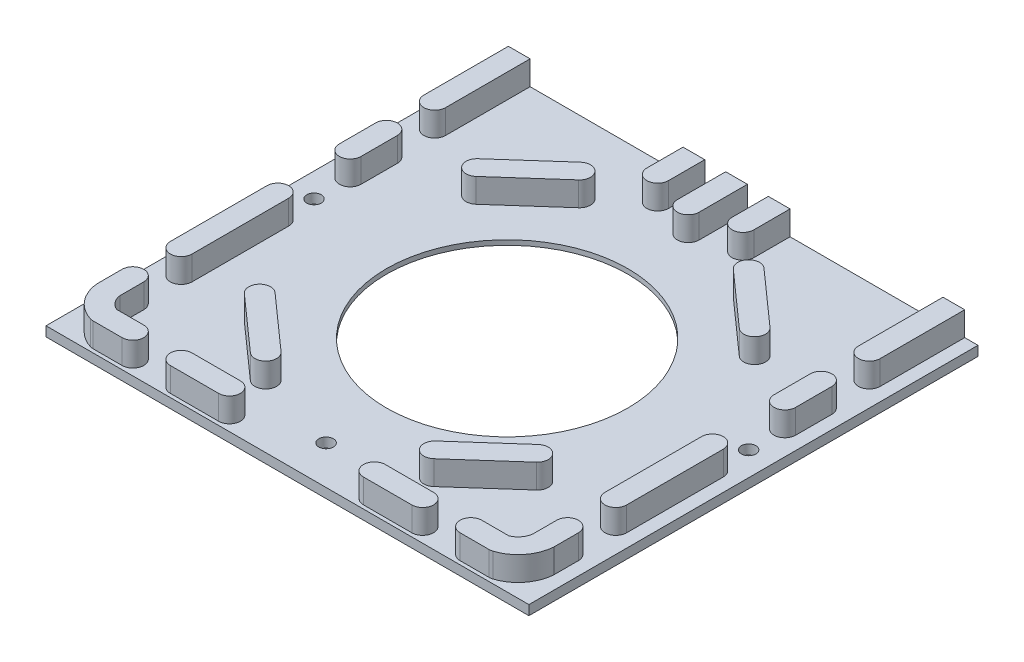
SolidWorks part; units mm, degrees
ref_plane "Front Plane" through (0, 0, 0) normal (0, 0, 1) x (1, 0, 0)
ref_plane "Top Plane" through (0, 0, 0) normal (0, 1, 0) x (1, 0, 0)
ref_plane "Right Plane" through (0, 0, 0) normal (1, 0, 0) x (0, 0, -1)
sketch "Sketch1" plane through (0, 0, 0) normal (0, 1, 0) x (1, 0, 0)
  line L1 (0, 0) -> (200, 0)
  line L2 (0, 0) -> (0, 190)
  line L3 (0, 190) -> (200, 190)
  line L4 (200, 0) -> (200, 190)
  dimension "D1" = 190
  dimension "D2" = 200
extrude "Boss-Extrude1" add sketch "Sketch1" along normal blind 4
sketch "Sketch3" plane through (0, 4, 0) normal (0, 1, 0) x (1, 0, 0)
  line L0 (0, 0) -> (18, 0)
  line L1 (0, 0) -> (200, 0) construction
  line L2 (18, 0) -> (18, 10)
  line L3 (0, 0) -> (0, 20)
  line L4 (0, 190) -> (0, 0) construction
  line L5 (0, 20) -> (10, 20)
  line L6 (10, 20) -> (10, 30) construction
  line L7 (5.5, 20) -> (5.5, 30)
  line L8 (14.5, 20) -> (14.5, 30)
  line L9 (18, 10) -> (30, 10) construction
  line L10 (18, 14.5) -> (30, 14.5)
  line L11 (18, 5.5) -> (30, 5.5)
  line L12 (0, 95) -> (200, 95) construction
  line L13 (200, 0) -> (200, 190) construction
  line L14 (100, 0) -> (100, 190) construction
  line L15 (200, 190) -> (0, 190) construction
  line L16 (10, 50) -> (10, 90) construction
  line L17 (5.5, 50) -> (5.5, 90)
  line L18 (14.5, 50) -> (14.5, 90)
  line L19 (50, 10) -> (70, 10) construction
  line L20 (50, 14.5) -> (70, 14.5)
  line L21 (50, 5.5) -> (70, 5.5)
  line L22 (190, 50) -> (190, 90) construction
  line L23 (194.5, 50) -> (194.5, 90)
  line L24 (185.5, 50) -> (185.5, 90)
  line L25 (190, 20) -> (190, 30) construction
  line L26 (194.5, 20) -> (194.5, 30)
  line L27 (185.5, 20) -> (185.5, 30)
  line L28 (182, 10) -> (170, 10) construction
  line L29 (182, 14.5) -> (170, 14.5)
  line L30 (182, 5.5) -> (170, 5.5)
  line L31 (150, 10) -> (130, 10) construction
  line L32 (150, 14.5) -> (130, 14.5)
  line L33 (150, 5.5) -> (130, 5.5)
  line L34 (10, 120) -> (10, 135) construction
  line L37 (157.5, 50) -> (135, 30) construction
  line L40 (154.5104, 53.3633) -> (132.0104, 33.3633)
  line L43 (160.4896, 46.6367) -> (137.9896, 26.6367)
  line L46 (157.5, 140) -> (135, 160) construction
  line L49 (154.5104, 136.6367) -> (132.0104, 156.6367)
  line L52 (160.4896, 143.3633) -> (137.9896, 163.3633)
  line L55 (5.5, 120) -> (5.5, 135)
  line L58 (200, 95) -> (200, 50) construction
  line L59 (200, 50) -> (0, 50) construction
  line L60 (200, 95) -> (200, 140) construction
  line L61 (200, 140) -> (0, 140) construction
  line L62 (42.5, 140) -> (65, 160) construction
  line L65 (45.4896, 136.6367) -> (67.9896, 156.6367)
  line L68 (39.5104, 143.3633) -> (62.0104, 163.3633)
  line L73 (42.5, 50) -> (65, 30) construction
  line L74 (45.4896, 53.3633) -> (67.9896, 33.3633)
  line L75 (39.5104, 46.6367) -> (62.0104, 26.6367)
  line L76 (100, 170) -> (100, 190) construction
  line L77 (95.5, 170) -> (95.5, 190)
  line L78 (104.5, 170) -> (104.5, 190)
  line L79 (82.3355, 175) -> (82.3355, 190) construction
  line L82 (77.8355, 175) -> (77.8355, 190)
  line L85 (10, 155) -> (10, 207.2046) construction
  line L86 (5.5, 155) -> (5.5, 207.2046)
  line L87 (14.5, 155) -> (14.5, 207.2046)
  line L88 (190, 155) -> (190, 207.2046) construction
  line L89 (194.5, 155) -> (194.5, 207.2046)
  line L90 (185.5, 155) -> (185.5, 207.2046)
  line L91 (86.8355, 175) -> (86.8355, 190)
  line L92 (117.6645, 175) -> (117.6645, 190) construction
  line L93 (122.1645, 175) -> (122.1645, 190)
  line L94 (113.1645, 175) -> (113.1645, 190)
  line L95 (14.5, 120) -> (14.5, 135)
  line L96 (190, 120) -> (190, 135) construction
  line L97 (194.5, 120) -> (194.5, 135)
  line L98 (185.5, 120) -> (185.5, 135)
  arc A1 (18, 10) -> (9.998, 20) centre (21.5097, 21.0101) cw construction
  arc A2 (5.5152, 19.6067) -> (16.6333, 5.7126) centre (21.5097, 21.0101) ccw
  arc A3 (14.4807, 20.3933) -> (19.3667, 14.2874) centre (21.5097, 21.0101) ccw
  arc A4 (14.4807, 20.3933) -> (5.5152, 19.6067) centre (9.998, 20) ccw
  arc A5 (16.6333, 5.7126) -> (19.3667, 14.2874) centre (18, 10) ccw
  arc A6 (5.5, 20) -> (14.5, 20) centre (10, 20) ccw
  arc A7 (14.5, 30) -> (5.5, 30) centre (10, 30) ccw
  arc A8 (18, 14.5) -> (18, 5.5) centre (18, 10) ccw
  arc A9 (30, 5.5) -> (30, 14.5) centre (30, 10) ccw
  arc A10 (5.5, 50) -> (14.5, 50) centre (10, 50) ccw
  arc A11 (14.5, 90) -> (5.5, 90) centre (10, 90) ccw
  arc A12 (50, 14.5) -> (50, 5.5) centre (50, 10) ccw
  arc A13 (70, 5.5) -> (70, 14.5) centre (70, 10) ccw
  arc A14 (194.5, 50) -> (185.5, 50) centre (190, 50) cw
  arc A15 (185.5, 90) -> (194.5, 90) centre (190, 90) cw
  arc A16 (194.5, 20) -> (185.5, 20) centre (190, 20) cw
  arc A17 (185.5, 30) -> (194.5, 30) centre (190, 30) cw
  arc A18 (182, 10) -> (190.002, 20) centre (178.4903, 21.0101) ccw construction
  arc A19 (194.4848, 19.6067) -> (183.3667, 5.7126) centre (178.4903, 21.0101) cw
  arc A20 (185.5193, 20.3933) -> (180.6333, 14.2874) centre (178.4903, 21.0101) cw
  arc A21 (185.5193, 20.3933) -> (194.4848, 19.6067) centre (190.002, 20) cw
  arc A22 (183.3667, 5.7126) -> (180.6333, 14.2874) centre (182, 10) cw
  arc A23 (182, 14.5) -> (182, 5.5) centre (182, 10) cw
  arc A24 (170, 5.5) -> (170, 14.5) centre (170, 10) cw
  arc A25 (150, 14.5) -> (150, 5.5) centre (150, 10) cw
  arc A26 (130, 5.5) -> (130, 14.5) centre (130, 10) cw
  circle A31 centre (100, 95) radius 50
  arc A44 (154.5104, 53.3633) -> (160.4896, 46.6367) centre (157.5, 50) cw
  arc A63 (45.4896, 53.3633) -> (39.5104, 46.6367) centre (42.5, 50) ccw
  arc A64 (62.0104, 26.6367) -> (67.9896, 33.3633) centre (65, 30) ccw
  arc A65 (137.9896, 26.6367) -> (132.0104, 33.3633) centre (135, 30) cw
  arc A66 (154.5104, 136.6367) -> (160.4896, 143.3633) centre (157.5, 140) ccw
  arc A67 (137.9896, 163.3633) -> (132.0104, 156.6367) centre (135, 160) ccw
  arc A68 (45.4896, 136.6367) -> (39.5104, 143.3633) centre (42.5, 140) cw
  arc A69 (62.0104, 163.3633) -> (67.9896, 156.6367) centre (65, 160) cw
  arc A70 (95.5, 170) -> (104.5, 170) centre (100, 170) ccw
  arc A71 (104.5, 190) -> (95.5, 190) centre (100, 190) ccw
  arc A76 (5.5, 155) -> (14.5, 155) centre (10, 155) ccw
  arc A77 (14.5, 207.2046) -> (5.5, 207.2046) centre (10, 207.2046) ccw
  arc A78 (194.5, 155) -> (185.5, 155) centre (190, 155) cw
  arc A79 (185.5, 207.2046) -> (194.5, 207.2046) centre (190, 207.2046) cw
  arc A80 (77.8355, 175) -> (86.8355, 175) centre (82.3355, 175) ccw
  arc A81 (86.8355, 190) -> (77.8355, 190) centre (82.3355, 190) ccw
  arc A82 (122.1645, 175) -> (113.1645, 175) centre (117.6645, 175) cw
  arc A83 (113.1645, 190) -> (122.1645, 190) centre (117.6645, 190) cw
  arc A84 (5.5, 120) -> (14.5, 120) centre (10, 120) ccw
  arc A85 (14.5, 135) -> (5.5, 135) centre (10, 135) ccw
  arc A86 (194.5, 120) -> (185.5, 120) centre (190, 120) cw
  arc A87 (185.5, 135) -> (194.5, 135) centre (190, 135) cw
  point P12 (12.4869, 13.79)
  point P17 (10, 25)
  point P25 (24, 10)
  point P40 (10, 70)
  point P47 (60, 10)
  point P54 (190, 70)
  point P61 (190, 25)
  point P69 (187.5131, 13.79)
  point P76 (176, 10)
  point P83 (140, 10)
  point P90 (10, 127.5)
  point P99 (146.25, 40)
  point P106 (146.25, 150)
  point P113 (53.75, 150)
  point P119 (100, 180)
  point P126 (82.3355, 182.5)
  point P133 (117.6645, 182.5)
  point P140 (10, 181.1023)
  point P147 (190, 181.1023)
  point P154 (190, 127.5)
  point P191 (53.75, 40)
  dimension "D4" = 4.5
  dimension "D8" = 4.5
  dimension "D11" = 4.5
  dimension "D16" = 100
  dimension "D19" = 4.5
  dimension "D22" = 4.5
  dimension "D24" = 16.0559
  dimension "D29" = 30
  dimension "D30" = 20
  dimension "D31" = 4.5
  dimension "D26" = 4.5
  dimension "D27" = 4.5
  dimension "D34" = 4.5
  dimension "D32" = 4.5
  dimension "D1" = 18
  dimension "D2" = 20
  dimension "D3" = 10
  dimension "D5" = 4.5
  dimension "D6" = 10
  dimension "D7" = 12
  dimension "D9" = 40
  dimension "D10" = 20
  dimension "D12" = 20
  dimension "D13" = 20
  dimension "D14" = 5
  dimension "D15" = 30
  dimension "D17" = 35
  dimension "D18" = 0
  dimension "D20" = 42.5
  dimension "D21" = 30
  dimension "D23" = 10
  dimension "D25" = 21.0101
  dimension "D28" = 15
  dimension "D33" = 15
  dimension "D35" = 35
extrude "Boss-Extrude2" add sketch "Sketch3" along normal blind 10
sketch "Sketch4" plane through (0, 0, 0) normal (0, 1, 0) x (1, 0, 0)
  line L0 (0, 0) -> (20, 0)
  line L1 (0, 0) -> (200, 0) construction
  line L2 (20, 0) -> (20, 10)
  line L3 (0, 0) -> (0, 20)
  line L5 (0, 20) -> (10, 20)
  line L6 (10, 20) -> (10, 30) construction
  line L7 (5, 20) -> (5, 30)
  line L8 (15, 20) -> (15, 30)
  line L9 (20, 10) -> (30, 10) construction
  line L10 (20, 15) -> (30, 15)
  line L11 (20, 5) -> (30, 5)
  line L12 (0, 95) -> (200, 95) construction
  line L14 (100, 0) -> (100, 170) construction
  line L16 (10, 50) -> (10, 72.5) construction
  line L17 (5, 50) -> (5, 72.5)
  line L18 (15, 50) -> (15, 72.5)
  line L19 (50, 10) -> (70, 10) construction
  line L20 (50, 15) -> (70, 15)
  line L21 (50, 5) -> (70, 5)
  line L22 (190, 50) -> (190, 72.5) construction
  line L23 (195, 50) -> (195, 72.5)
  line L24 (185, 50) -> (185, 72.5)
  line L25 (190, 20) -> (190, 30) construction
  line L26 (195, 20) -> (195, 30)
  line L27 (185, 20) -> (185, 30)
  line L28 (180, 10) -> (170, 10) construction
  line L29 (180, 15) -> (170, 15)
  line L30 (180, 5) -> (170, 5)
  line L31 (150, 10) -> (130, 10) construction
  line L32 (150, 15) -> (130, 15)
  line L33 (150, 5) -> (130, 5)
  line L34 (190, 140) -> (190, 117.5) construction
  line L35 (195, 140) -> (195, 117.5)
  line L36 (185, 140) -> (185, 117.5)
  line L37 (157.5, 50) -> (135, 30) construction
  line L40 (154.1782, 53.737) -> (131.6782, 33.737)
  line L43 (160.8218, 46.263) -> (138.3218, 26.263)
  line L46 (157.5, 140) -> (135, 160) construction
  line L49 (154.1782, 136.263) -> (131.6782, 156.263)
  line L52 (160.8218, 143.737) -> (138.3218, 163.737)
  line L55 (10, 140) -> (10, 117.5) construction
  line L56 (5, 140) -> (5, 117.5)
  line L57 (15, 140) -> (15, 117.5)
  line L58 (200, 95) -> (200, 50) construction
  line L59 (200, 50) -> (0, 50) construction
  line L60 (200, 95) -> (200, 140) construction
  line L61 (200, 140) -> (0, 140) construction
  line L62 (42.5, 140) -> (65, 160) construction
  line L65 (45.8218, 136.263) -> (68.3218, 156.263)
  line L68 (39.1782, 143.737) -> (61.6782, 163.737)
  line L73 (42.5, 50) -> (65, 30) construction
  line L74 (45.8218, 53.737) -> (68.3218, 33.737)
  line L75 (39.1782, 46.263) -> (61.6782, 26.263)
  line L76 (100, 150) -> (100, 170) construction
  line L77 (95, 150) -> (95, 170)
  line L78 (105, 150) -> (105, 170)
  line L79 (82.3355, 155) -> (82.3355, 170) construction
  line L82 (77.3355, 155) -> (77.3355, 170)
  line L85 (10, 165) -> (10, 207.2046) construction
  line L86 (5, 165) -> (5, 207.2046)
  line L87 (15, 165) -> (15, 207.2046)
  line L88 (190, 165) -> (190, 207.2046) construction
  line L89 (195, 165) -> (195, 207.2046)
  line L90 (185, 165) -> (185, 207.2046)
  line L91 (87.3355, 155) -> (87.3355, 170)
  line L92 (117.6645, 155) -> (117.6645, 170) construction
  line L93 (122.6645, 155) -> (122.6645, 170)
  line L94 (112.6645, 155) -> (112.6645, 170)
  arc A1 (20, 10) -> (9.9962, 20) centre (21.0059, 21.0101) cw construction
  arc A2 (5.0171, 19.5432) -> (19.5451, 5.0207) centre (21.0059, 21.0101) ccw
  arc A3 (14.9753, 20.4568) -> (20.4549, 14.9793) centre (21.0059, 21.0101) ccw
  arc A4 (14.9753, 20.4568) -> (5.0171, 19.5432) centre (9.9962, 20) ccw
  arc A5 (19.5451, 5.0207) -> (20.4549, 14.9793) centre (20, 10) ccw
  arc A6 (5, 20) -> (15, 20) centre (10, 20) ccw
  arc A7 (15, 30) -> (5, 30) centre (10, 30) ccw
  arc A8 (20, 15) -> (20, 5) centre (20, 10) ccw
  arc A9 (30, 5) -> (30, 15) centre (30, 10) ccw
  arc A10 (5, 50) -> (15, 50) centre (10, 50) ccw
  arc A11 (15, 72.5) -> (5, 72.5) centre (10, 72.5) ccw
  arc A12 (50, 15) -> (50, 5) centre (50, 10) ccw
  arc A13 (70, 5) -> (70, 15) centre (70, 10) ccw
  arc A14 (195, 50) -> (185, 50) centre (190, 50) cw
  arc A15 (185, 72.5) -> (195, 72.5) centre (190, 72.5) cw
  arc A16 (195, 20) -> (185, 20) centre (190, 20) cw
  arc A17 (185, 30) -> (195, 30) centre (190, 30) cw
  arc A18 (180, 10) -> (190.0038, 20) centre (178.9941, 21.0101) ccw construction
  arc A19 (194.9829, 19.5432) -> (180.4549, 5.0207) centre (178.9941, 21.0101) cw
  arc A20 (185.0247, 20.4568) -> (179.5451, 14.9793) centre (178.9941, 21.0101) cw
  arc A21 (185.0247, 20.4568) -> (194.9829, 19.5432) centre (190.0038, 20) cw
  arc A22 (180.4549, 5.0207) -> (179.5451, 14.9793) centre (180, 10) cw
  arc A23 (180, 15) -> (180, 5) centre (180, 10) cw
  arc A24 (170, 5) -> (170, 15) centre (170, 10) cw
  arc A25 (150, 15) -> (150, 5) centre (150, 10) cw
  arc A26 (130, 5) -> (130, 15) centre (130, 10) cw
  arc A27 (195, 140) -> (185, 140) centre (190, 140) ccw
  arc A28 (185, 117.5) -> (195, 117.5) centre (190, 117.5) ccw
  circle A31 centre (100, 95) radius 50
  arc A44 (154.1782, 53.737) -> (160.8218, 46.263) centre (157.5, 50) cw
  arc A51 (5, 140) -> (15, 140) centre (10, 140) cw
  arc A52 (15, 117.5) -> (5, 117.5) centre (10, 117.5) cw
  arc A63 (45.8218, 53.737) -> (39.1782, 46.263) centre (42.5, 50) ccw
  arc A64 (61.6782, 26.263) -> (68.3218, 33.737) centre (65, 30) ccw
  arc A65 (138.3218, 26.263) -> (131.6782, 33.737) centre (135, 30) cw
  arc A66 (154.1782, 136.263) -> (160.8218, 143.737) centre (157.5, 140) ccw
  arc A67 (138.3218, 163.737) -> (131.6782, 156.263) centre (135, 160) ccw
  arc A68 (45.8218, 136.263) -> (39.1782, 143.737) centre (42.5, 140) cw
  arc A69 (61.6782, 163.737) -> (68.3218, 156.263) centre (65, 160) cw
  arc A70 (95, 150) -> (105, 150) centre (100, 150) ccw
  arc A71 (105, 170) -> (95, 170) centre (100, 170) ccw
  arc A76 (5, 165) -> (15, 165) centre (10, 165) ccw
  arc A77 (15, 207.2046) -> (5, 207.2046) centre (10, 207.2046) ccw
  arc A78 (195, 165) -> (185, 165) centre (190, 165) cw
  arc A79 (185, 207.2046) -> (195, 207.2046) centre (190, 207.2046) cw
  arc A80 (77.3355, 155) -> (87.3355, 155) centre (82.3355, 155) ccw
  arc A81 (87.3355, 170) -> (77.3355, 170) centre (82.3355, 170) ccw
  arc A82 (122.6645, 155) -> (112.6645, 155) centre (117.6645, 155) cw
  arc A83 (112.6645, 170) -> (122.6645, 170) centre (117.6645, 170) cw
  point P12 (13.1897, 13.1909)
  point P17 (10, 25)
  point P25 (25, 10)
  point P40 (10, 61.25)
  point P47 (60, 10)
  point P54 (190, 61.25)
  point P61 (190, 25)
  point P69 (186.8103, 13.1909)
  point P76 (175, 10)
  point P83 (140, 10)
  point P90 (190, 128.75)
  point P99 (146.25, 40)
  point P106 (146.25, 150)
  point P113 (53.75, 150)
  point P119 (100, 160)
  point P126 (82.3355, 162.5)
  point P133 (117.6645, 162.5)
  point P140 (10, 186.1023)
  point P147 (190, 186.1023)
  point P155 (10, 128.75)
  point P191 (53.75, 40)
  dimension "D4" = 5
  dimension "D8" = 5
  dimension "D11" = 5
  dimension "D16" = 100
  dimension "D19" = 5
  dimension "D22" = 5
  dimension "D24" = 16.0559
  dimension "D31" = 5
  dimension "D26" = 5
  dimension "D27" = 5
  dimension "D20" = 95
  dimension "D1" = 20
  dimension "D2" = 20
  dimension "D3" = 10
  dimension "D5" = 5
  dimension "D6" = 10
  dimension "D7" = 10
  dimension "D9" = 22.5
  dimension "D10" = 20
  dimension "D12" = 20
  dimension "D13" = 20
  dimension "D14" = 22.5
  dimension "D15" = 30
  dimension "D17" = 35
  dimension "D18" = 0
  dimension "D28" = 15
  dimension "D32" = 25
extrude "Cut-Extrude1" cut sketch "Sketch4" along normal blind 10 contours A31
sketch "Sketch6" plane through (0, 0, 0) normal (0, 1, 0) x (1, 0, 0)
  line L0 (0, 0) -> (20, 0)
  line L1 (0, 0) -> (200, 0) construction
  line L2 (20, 0) -> (20, 10)
  line L3 (0, 0) -> (0, 20)
  line L5 (0, 20) -> (10, 20)
  line L6 (10, 20) -> (10, 30) construction
  line L7 (5, 20) -> (5, 30)
  line L8 (15, 20) -> (15, 30)
  line L9 (20, 10) -> (30, 10) construction
  line L10 (20, 15) -> (30, 15)
  line L11 (20, 5) -> (30, 5)
  line L12 (0, 95) -> (200, 95) construction
  line L14 (100, 0) -> (100, 170) construction
  line L16 (10, 50) -> (10, 72.5) construction
  line L17 (5, 50) -> (5, 72.5)
  line L18 (15, 50) -> (15, 72.5)
  line L19 (50, 10) -> (70, 10) construction
  line L20 (50, 15) -> (70, 15)
  line L21 (50, 5) -> (70, 5)
  line L22 (190, 50) -> (190, 72.5) construction
  line L23 (195, 50) -> (195, 72.5)
  line L24 (185, 50) -> (185, 72.5)
  line L25 (190, 20) -> (190, 30) construction
  line L26 (195, 20) -> (195, 30)
  line L27 (185, 20) -> (185, 30)
  line L28 (180, 10) -> (170, 10) construction
  line L29 (180, 15) -> (170, 15)
  line L30 (180, 5) -> (170, 5)
  line L31 (150, 10) -> (130, 10) construction
  line L32 (150, 15) -> (130, 15)
  line L33 (150, 5) -> (130, 5)
  line L34 (190, 140) -> (190, 117.5) construction
  line L35 (195, 140) -> (195, 117.5)
  line L36 (185, 140) -> (185, 117.5)
  line L37 (157.5, 50) -> (135, 30) construction
  line L40 (154.1782, 53.737) -> (131.6782, 33.737)
  line L43 (160.8218, 46.263) -> (138.3218, 26.263)
  line L46 (157.5, 140) -> (135, 160) construction
  line L49 (154.1782, 136.263) -> (131.6782, 156.263)
  line L52 (160.8218, 143.737) -> (138.3218, 163.737)
  line L55 (10, 140) -> (10, 117.5) construction
  line L56 (5, 140) -> (5, 117.5)
  line L57 (15, 140) -> (15, 117.5)
  line L58 (200, 95) -> (200, 50) construction
  line L59 (200, 50) -> (0, 50) construction
  line L60 (200, 95) -> (200, 140) construction
  line L61 (200, 140) -> (0, 140) construction
  line L62 (42.5, 140) -> (65, 160) construction
  line L65 (45.8218, 136.263) -> (68.3218, 156.263)
  line L68 (39.1782, 143.737) -> (61.6782, 163.737)
  line L73 (42.5, 50) -> (65, 30) construction
  line L74 (45.8218, 53.737) -> (68.3218, 33.737)
  line L75 (39.1782, 46.263) -> (61.6782, 26.263)
  line L76 (100, 150) -> (100, 170) construction
  line L77 (95, 150) -> (95, 170)
  line L78 (105, 150) -> (105, 170)
  line L79 (82.3355, 155) -> (82.3355, 170) construction
  line L82 (77.3355, 155) -> (77.3355, 170)
  line L85 (10, 165) -> (10, 207.2046) construction
  line L86 (5, 165) -> (5, 207.2046)
  line L87 (15, 165) -> (15, 207.2046)
  line L88 (190, 165) -> (190, 207.2046) construction
  line L89 (195, 165) -> (195, 207.2046)
  line L90 (185, 165) -> (185, 207.2046)
  line L91 (87.3355, 155) -> (87.3355, 170)
  line L92 (117.6645, 155) -> (117.6645, 170) construction
  line L93 (122.6645, 155) -> (122.6645, 170)
  line L94 (112.6645, 155) -> (112.6645, 170)
  arc A1 (20, 10) -> (9.9962, 20) centre (21.0059, 21.0101) cw construction
  arc A2 (5.0171, 19.5432) -> (19.5451, 5.0207) centre (21.0059, 21.0101) ccw
  arc A3 (14.9753, 20.4568) -> (20.4549, 14.9793) centre (21.0059, 21.0101) ccw
  arc A4 (14.9753, 20.4568) -> (5.0171, 19.5432) centre (9.9962, 20) ccw
  arc A5 (19.5451, 5.0207) -> (20.4549, 14.9793) centre (20, 10) ccw
  arc A6 (5, 20) -> (15, 20) centre (10, 20) ccw
  arc A7 (15, 30) -> (5, 30) centre (10, 30) ccw
  arc A8 (20, 15) -> (20, 5) centre (20, 10) ccw
  arc A9 (30, 5) -> (30, 15) centre (30, 10) ccw
  arc A10 (5, 50) -> (15, 50) centre (10, 50) ccw
  arc A11 (15, 72.5) -> (5, 72.5) centre (10, 72.5) ccw
  arc A12 (50, 15) -> (50, 5) centre (50, 10) ccw
  arc A13 (70, 5) -> (70, 15) centre (70, 10) ccw
  arc A14 (195, 50) -> (185, 50) centre (190, 50) cw
  arc A15 (185, 72.5) -> (195, 72.5) centre (190, 72.5) cw
  arc A16 (195, 20) -> (185, 20) centre (190, 20) cw
  arc A17 (185, 30) -> (195, 30) centre (190, 30) cw
  arc A18 (180, 10) -> (190.0038, 20) centre (178.9941, 21.0101) ccw construction
  arc A19 (194.9829, 19.5432) -> (180.4549, 5.0207) centre (178.9941, 21.0101) cw
  arc A20 (185.0247, 20.4568) -> (179.5451, 14.9793) centre (178.9941, 21.0101) cw
  arc A21 (185.0247, 20.4568) -> (194.9829, 19.5432) centre (190.0038, 20) cw
  arc A22 (180.4549, 5.0207) -> (179.5451, 14.9793) centre (180, 10) cw
  arc A23 (180, 15) -> (180, 5) centre (180, 10) cw
  arc A24 (170, 5) -> (170, 15) centre (170, 10) cw
  arc A25 (150, 15) -> (150, 5) centre (150, 10) cw
  arc A26 (130, 5) -> (130, 15) centre (130, 10) cw
  arc A27 (195, 140) -> (185, 140) centre (190, 140) ccw
  arc A28 (185, 117.5) -> (195, 117.5) centre (190, 117.5) ccw
  circle A31 centre (100, 95) radius 57.5
  arc A44 (154.1782, 53.737) -> (160.8218, 46.263) centre (157.5, 50) cw
  arc A51 (5, 140) -> (15, 140) centre (10, 140) cw
  arc A52 (15, 117.5) -> (5, 117.5) centre (10, 117.5) cw
  arc A63 (45.8218, 53.737) -> (39.1782, 46.263) centre (42.5, 50) ccw
  arc A64 (61.6782, 26.263) -> (68.3218, 33.737) centre (65, 30) ccw
  arc A65 (138.3218, 26.263) -> (131.6782, 33.737) centre (135, 30) cw
  arc A66 (154.1782, 136.263) -> (160.8218, 143.737) centre (157.5, 140) ccw
  arc A67 (138.3218, 163.737) -> (131.6782, 156.263) centre (135, 160) ccw
  arc A68 (45.8218, 136.263) -> (39.1782, 143.737) centre (42.5, 140) cw
  arc A69 (61.6782, 163.737) -> (68.3218, 156.263) centre (65, 160) cw
  arc A70 (95, 150) -> (105, 150) centre (100, 150) ccw
  arc A71 (105, 170) -> (95, 170) centre (100, 170) ccw
  arc A76 (5, 165) -> (15, 165) centre (10, 165) ccw
  arc A77 (15, 207.2046) -> (5, 207.2046) centre (10, 207.2046) ccw
  arc A78 (195, 165) -> (185, 165) centre (190, 165) cw
  arc A79 (185, 207.2046) -> (195, 207.2046) centre (190, 207.2046) cw
  arc A80 (77.3355, 155) -> (87.3355, 155) centre (82.3355, 155) ccw
  arc A81 (87.3355, 170) -> (77.3355, 170) centre (82.3355, 170) ccw
  arc A82 (122.6645, 155) -> (112.6645, 155) centre (117.6645, 155) cw
  arc A83 (112.6645, 170) -> (122.6645, 170) centre (117.6645, 170) cw
  point P12 (13.1897, 13.1909)
  point P17 (10, 25)
  point P25 (25, 10)
  point P40 (10, 61.25)
  point P47 (60, 10)
  point P54 (190, 61.25)
  point P61 (190, 25)
  point P69 (186.8103, 13.1909)
  point P76 (175, 10)
  point P83 (140, 10)
  point P90 (190, 128.75)
  point P99 (146.25, 40)
  point P106 (146.25, 150)
  point P113 (53.75, 150)
  point P119 (100, 160)
  point P126 (82.3355, 162.5)
  point P133 (117.6645, 162.5)
  point P140 (10, 186.1023)
  point P147 (190, 186.1023)
  point P155 (10, 128.75)
  point P191 (53.75, 40)
  dimension "D4" = 5
  dimension "D8" = 5
  dimension "D11" = 5
  dimension "D16" = 115
  dimension "D19" = 5
  dimension "D22" = 5
  dimension "D24" = 16.0559
  dimension "D31" = 5
  dimension "D26" = 5
  dimension "D27" = 5
  dimension "D20" = 95
  dimension "D1" = 20
  dimension "D2" = 20
  dimension "D3" = 10
  dimension "D5" = 5
  dimension "D6" = 10
  dimension "D7" = 10
  dimension "D9" = 22.5
  dimension "D10" = 20
  dimension "D12" = 20
  dimension "D13" = 20
  dimension "D14" = 22.5
  dimension "D15" = 30
  dimension "D17" = 35
  dimension "D18" = 0
  dimension "D28" = 15
  dimension "D32" = 25
sketch "Sketch9" plane through (0, 0, 0) normal (0, -1, 0) x (1, 0, 0)
  line L0 (200, 0) -> (200, -190) construction
  line L1 (0, 0) -> (200, 0)
  line L2 (0, 0) -> (0, -4)
  line L3 (0, -4) -> (200, -4)
  line L4 (200, 0) -> (200, -4)
  dimension "D1" = 4
extrude "Cut-Extrude6" cut sketch "Sketch9" against normal blind 12
sketch "Sketch10" plane through (0, 4, 0) normal (0, 1, 0) x (1, 0, 0)
  line L0 (100, 4) -> (100, 181.9251) construction
  line L1 (0, 4) -> (200, 4) construction
  line L2 (0, 190) -> (0, 4) construction
  line L3 (77.8355, 190) -> (14.5, 190) construction
  circle A0 centre (10, 105) radius 3
  circle A2 centre (100, 20) radius 3
  circle A3 centre (190, 105) radius 3
  dimension "D2" = 6
  dimension "D3" = 10
  dimension "D6" = 85
  dimension "D7" = 6
  dimension "D8" = 20
  dimension "D9" = 101
  dimension "D11" = 101
  dimension "D13" = 105
ref_plane "Plane1" through (0, 0, 0) normal (0, -1, 0) x (-1, 0, 0)
sketch "Sketch12" plane through (0, 0, 0) normal (0, -1, 0) x (-1, 0, 0)
  line L0 (-129.6166, -38.234) -> (-109.6166, -38.234)
  line L1 (-109.6166, -38.234) -> (-109.6166, -28.234)
  line L2 (-129.6166, -38.234) -> (-129.6166, -18.234)
  line L3 (-129.6166, -18.234) -> (-119.6166, -18.234)
  line L4 (-119.6166, -18.234) -> (-119.6166, -8.234) construction
  line L5 (-124.6166, -18.234) -> (-124.6166, -8.234)
  line L6 (-114.6166, -18.234) -> (-114.6166, -8.234)
  line L7 (-109.6166, -28.234) -> (-99.6166, -28.234) construction
  line L8 (-109.6166, -23.234) -> (-99.6166, -23.234)
  line L9 (-109.6166, -33.234) -> (-99.6166, -33.234)
  line L10 (-270.3834, 95) -> (70.3834, 95) construction
  line L11 (-29.6166, -38.234) -> (-29.6166, 131.766) construction
  line L12 (-119.6166, 11.766) -> (-119.6166, 34.266) construction
  line L13 (-124.6166, 11.766) -> (-124.6166, 34.266)
  line L14 (-114.6166, 11.766) -> (-114.6166, 34.266)
  line L15 (-79.6166, -28.234) -> (-59.6166, -28.234) construction
  line L16 (-79.6166, -23.234) -> (-59.6166, -23.234)
  line L17 (-79.6166, -33.234) -> (-59.6166, -33.234)
  line L18 (60.3834, 11.766) -> (60.3834, 34.266) construction
  line L19 (65.3834, 11.766) -> (65.3834, 34.266)
  line L20 (55.3834, 11.766) -> (55.3834, 34.266)
  line L21 (60.3834, -18.234) -> (60.3834, -8.234) construction
  line L22 (65.3834, -18.234) -> (65.3834, -8.234)
  line L23 (55.3834, -18.234) -> (55.3834, -8.234)
  line L24 (50.3834, -28.234) -> (40.3834, -28.234) construction
  line L25 (50.3834, -23.234) -> (40.3834, -23.234)
  line L26 (50.3834, -33.234) -> (40.3834, -33.234)
  line L27 (20.3834, -28.234) -> (0.3834, -28.234) construction
  line L28 (20.3834, -23.234) -> (0.3834, -23.234)
  line L29 (20.3834, -33.234) -> (0.3834, -33.234)
  line L30 (60.3834, 178.234) -> (60.3834, 155.734) construction
  line L31 (65.3834, 178.234) -> (65.3834, 155.734)
  line L32 (55.3834, 178.234) -> (55.3834, 155.734)
  line L33 (27.8834, 11.766) -> (5.3834, -8.234) construction
  line L34 (24.5616, 15.503) -> (2.0616, -4.497)
  line L35 (31.2052, 8.0289) -> (8.7052, -11.9711)
  line L36 (27.8834, 178.234) -> (5.3834, 198.234) construction
  line L37 (24.5616, 174.497) -> (2.0616, 194.497)
  line L38 (31.2052, 181.9711) -> (8.7052, 201.9711)
  line L39 (-119.6166, 178.234) -> (-119.6166, 155.734) construction
  line L40 (-124.6166, 178.234) -> (-124.6166, 155.734)
  line L41 (-114.6166, 178.234) -> (-114.6166, 155.734)
  line L42 (70.3834, 95) -> (70.3834, 11.766) construction
  line L43 (70.3834, 11.766) -> (-129.6166, 11.766) construction
  line L44 (70.3834, 95) -> (70.3834, 178.234) construction
  line L45 (70.3834, 178.234) -> (-129.6166, 178.234) construction
  line L46 (-87.1166, 178.234) -> (-64.6166, 198.234) construction
  line L47 (-83.7948, 174.497) -> (-61.2948, 194.497)
  line L48 (-90.4384, 181.9711) -> (-67.9384, 201.9711)
  line L49 (-87.1166, 11.766) -> (-64.6166, -8.234) construction
  line L50 (-83.7948, 15.503) -> (-61.2948, -4.497)
  line L51 (-90.4384, 8.0289) -> (-67.9384, -11.9711)
  line L60 (60.3834, 126.766) -> (60.3834, 168.9706) construction
  line L61 (65.3834, 126.766) -> (65.3834, 168.9706)
  line L62 (55.3834, 126.766) -> (55.3834, 168.9706)
  line L64 (-11.9521, 116.766) -> (-11.9521, 131.766) construction
  line L65 (-6.9521, 116.766) -> (-6.9521, 131.766)
  line L66 (-16.9521, 116.766) -> (-16.9521, 131.766)
  arc A0 (-109.6166, -28.234) -> (-119.6204, -18.234) centre (-108.6107, -17.2239) cw construction
  arc A1 (-124.5995, -18.6908) -> (-110.0715, -33.2133) centre (-108.6107, -17.2239) ccw
  arc A2 (-114.6413, -17.7772) -> (-109.1617, -23.2548) centre (-108.6107, -17.2239) ccw
  arc A3 (-114.6413, -17.7772) -> (-124.5995, -18.6908) centre (-119.6204, -18.234) ccw
  arc A4 (-110.0715, -33.2133) -> (-109.1617, -23.2548) centre (-109.6166, -28.234) ccw
  arc A5 (-124.6166, -18.234) -> (-114.6166, -18.234) centre (-119.6166, -18.234) ccw
  arc A6 (-114.6166, -8.234) -> (-124.6166, -8.234) centre (-119.6166, -8.234) ccw
  arc A7 (-109.6166, -23.234) -> (-109.6166, -33.234) centre (-109.6166, -28.234) ccw
  arc A8 (-99.6166, -33.234) -> (-99.6166, -23.234) centre (-99.6166, -28.234) ccw
  arc A9 (-124.6166, 11.766) -> (-114.6166, 11.766) centre (-119.6166, 11.766) ccw
  arc A10 (-114.6166, 34.266) -> (-124.6166, 34.266) centre (-119.6166, 34.266) ccw
  arc A11 (-79.6166, -23.234) -> (-79.6166, -33.234) centre (-79.6166, -28.234) ccw
  arc A12 (-59.6166, -33.234) -> (-59.6166, -23.234) centre (-59.6166, -28.234) ccw
  arc A13 (65.3834, 11.766) -> (55.3834, 11.766) centre (60.3834, 11.766) cw
  arc A14 (55.3834, 34.266) -> (65.3834, 34.266) centre (60.3834, 34.266) cw
  arc A15 (65.3834, -18.234) -> (55.3834, -18.234) centre (60.3834, -18.234) cw
  arc A16 (55.3834, -8.234) -> (65.3834, -8.234) centre (60.3834, -8.234) cw
  arc A17 (50.3834, -28.234) -> (60.3872, -18.234) centre (49.3775, -17.2239) ccw construction
  arc A18 (65.3663, -18.6908) -> (50.8383, -33.2133) centre (49.3775, -17.2239) cw
  arc A19 (55.4081, -17.7772) -> (49.9285, -23.2548) centre (49.3775, -17.2239) cw
  arc A20 (55.4081, -17.7772) -> (65.3663, -18.6908) centre (60.3872, -18.234) cw
  arc A21 (50.8383, -33.2133) -> (49.9285, -23.2548) centre (50.3834, -28.234) cw
  arc A22 (50.3834, -23.234) -> (50.3834, -33.234) centre (50.3834, -28.234) cw
  arc A23 (40.3834, -33.234) -> (40.3834, -23.234) centre (40.3834, -28.234) cw
  arc A24 (20.3834, -23.234) -> (20.3834, -33.234) centre (20.3834, -28.234) cw
  arc A25 (0.3834, -33.234) -> (0.3834, -23.234) centre (0.3834, -28.234) cw
  arc A26 (65.3834, 178.234) -> (55.3834, 178.234) centre (60.3834, 178.234) ccw
  arc A27 (55.3834, 155.734) -> (65.3834, 155.734) centre (60.3834, 155.734) ccw
  circle A28 centre (-100, 95) radius 57.5
  arc A29 (24.5616, 15.503) -> (31.2052, 8.0289) centre (27.8834, 11.766) cw
  arc A30 (-124.6166, 178.234) -> (-114.6166, 178.234) centre (-119.6166, 178.234) cw
  arc A31 (-114.6166, 155.734) -> (-124.6166, 155.734) centre (-119.6166, 155.734) cw
  arc A32 (-83.7948, 15.503) -> (-90.4384, 8.0289) centre (-87.1166, 11.766) ccw
  arc A33 (-67.9384, -11.9711) -> (-61.2948, -4.497) centre (-64.6166, -8.234) ccw
  arc A34 (8.7052, -11.9711) -> (2.0616, -4.497) centre (5.3834, -8.234) cw
  arc A35 (24.5616, 174.497) -> (31.2052, 181.9711) centre (27.8834, 178.234) ccw
  arc A36 (8.7052, 201.9711) -> (2.0616, 194.497) centre (5.3834, 198.234) ccw
  arc A37 (-83.7948, 174.497) -> (-90.4384, 181.9711) centre (-87.1166, 178.234) cw
  arc A38 (-67.9384, 201.9711) -> (-61.2948, 194.497) centre (-64.6166, 198.234) cw
  arc A43 (65.3834, 126.766) -> (55.3834, 126.766) centre (60.3834, 126.766) cw
  arc A44 (55.3834, 168.9706) -> (65.3834, 168.9706) centre (60.3834, 168.9706) cw
  arc A47 (-6.9521, 116.766) -> (-16.9521, 116.766) centre (-11.9521, 116.766) cw
  arc A48 (-16.9521, 131.766) -> (-6.9521, 131.766) centre (-11.9521, 131.766) cw
  point P7 (-116.427, -25.0432)
  point P12 (-119.6166, -13.234)
  point P20 (-104.6166, -28.234)
  point P31 (-119.6166, 23.016)
  point P38 (-69.6166, -28.234)
  point P45 (60.3834, 23.016)
  point P52 (60.3834, -13.234)
  point P60 (57.1937, -25.0432)
  point P67 (45.3834, -28.234)
  point P74 (10.3834, -28.234)
  point P81 (60.3834, 166.984)
  point P90 (16.6334, 1.766)
  point P97 (16.6334, 188.234)
  point P104 (-75.8666, 188.234)
  point P124 (-11.9521, 124.266)
  point P138 (60.3834, 147.8683)
  point P145 (-119.6166, 166.984)
  point P156 (-75.8666, 1.766)
extrude "Cut-Extrude7" cut sketch "Sketch12" against normal blind 2
extrude "Cut-Extrude8" cut sketch "Sketch10" against normal blind 10
sketch "Sketch13" plane through (0, 0, 0) normal (0, -1, 0) x (1, 0, 0)
  line L0 (0, -190) -> (0, -4) construction
  line L9 (152.4978, -42.5022) -> (47.5, -42.5022)
  line L10 (152.4978, -42.5022) -> (152.4978, -147.5)
  line L11 (152.4978, -147.5) -> (47.5, -147.5)
  line L12 (47.5, -42.5022) -> (47.5, -147.5)
  line L14 (200, -4) -> (200, -190) construction
  line L15 (200, -190) -> (0, -190) construction
  line L16 (0, -4) -> (200, -4) construction
  circle A1 centre (100, -95) radius 50 construction
  circle A2 centre (152.4978, -42.5022) radius 2
  circle A3 centre (152.4978, -147.5) radius 2
  circle A4 centre (47.5, -147.5) radius 2
  circle A5 centre (47.5, -42.5022) radius 2
  dimension "D6" = 52.5
  dimension "D7" = 52.5
  dimension "D8" = 52.4978
  dimension "D9" = 4
  dimension "D10" = 4
  dimension "D11" = 4
  dimension "D12" = 4
  dimension "D1" = 47.5
  dimension "D2" = 47.5022
  dimension "D3" = 42.5
  dimension "D4" = 38.5022
  dimension "D5" = 52.4978
extrude "Cut-Extrude9" cut sketch "Sketch13" against normal blind 10 contours L12 A4 L11 | L11 A4 L12 | L9 A5 L12 | L12 A5 L9 | L10 A2 L9 | L9 A2 L10 | L11 A3 L10 | L10 A3 L11
